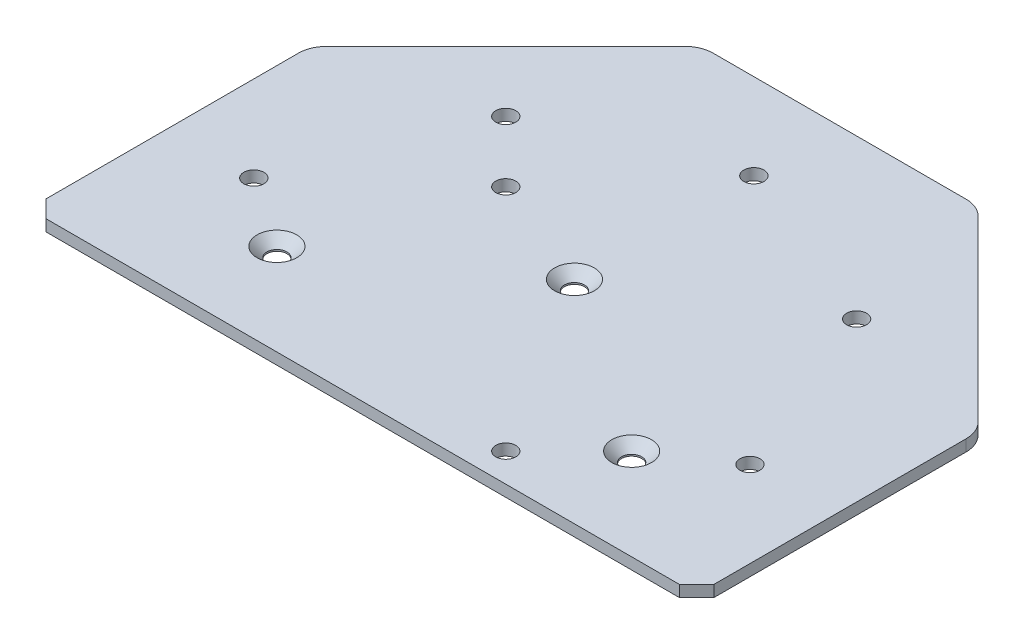
SolidWorks part; units mm, degrees
material "1060 Alloy"
ref_plane "Front Plane" through (0, 0, 0) normal (0, 0, 1) x (1, 0, 0)
ref_plane "Top Plane" through (0, 0, 0) normal (0, 1, 0) x (1, 0, 0)
ref_plane "Right Plane" through (0, 0, 0) normal (1, 0, 0) x (0, 0, -1)
sketch "Sketch2" plane through (0, 0, 0) normal (0, 1, 0) x (1, 0, 0)
  line L0 (-58.3553, 0) -> (58.3553, 0)
  line L1 (58.3553, 0) -> (58.3553, 49.1716)
  line L2 (58.3553, 49.1716) -> (24.1716, 83.3553)
  line L3 (24.1716, 83.3553) -> (-24.1716, 83.3553)
  line L4 (0, 83.3553) -> (0, 0) construction
  line L5 (-58.3553, 49.1716) -> (-24.1716, 83.3553)
  line L6 (-58.3553, 0) -> (-58.3553, 49.1716)
  line L7 (-57.9727, 49.5543) -> (-24.5543, 82.9727) construction
  line L8 (23.6304, 83.3553) -> (-23.6304, 83.3553) construction
extrude "Boss-Extrude1" add sketch "Sketch2" along normal blind 2
sketch "Sketch3" plane through (0, 0, 0) normal (0, -1, 0) x (1, 0, 0)
  circle A0 centre (-43.3553, -24.3152) radius 1.75
  circle A1 centre (-30.6569, -55.6569) radius 1.75
  circle A2 centre (0, -68.3553) radius 1.75
  circle A3 centre (30.6569, -55.6569) radius 1.75
  circle A4 centre (43.3553, -24.3152) radius 1.75
  dimension "D1" = 3.5
extrude "Cut-Extrude1" cut sketch "Sketch3" against normal up to next
chamfer "Chamfer1" distance 3 angle 45 2 edges at (58.3553, 1, 0) (-58.3553, 1, 0)
fillet "Fillet1" radius 5 4 edges at (58.3553, 1, -49.1716) (24.1716, 1, -83.3553) (-24.1716, 1, -83.3553) (-58.3553, 1, -49.1716)
sketch "Sketch4" plane through (0, 2, 0) normal (0, 1, 0) x (1, 0, 0)
  line L0 (0, 0) -> (0, 45) construction
  line L1 (0, 45) -> (-20, 45) construction
  line L2 (0, 5) -> (20, 5) construction
  line L4 (-55.3553, 0) -> (55.3553, 0) construction
  circle A0 centre (-20, 45) radius 1.75
  circle A1 centre (20, 5) radius 1.75
  dimension "D2" = 3.5
  dimension "D3" = 40
  dimension "D1" = 40
  dimension "D4" = 5
extrude "Cut-Extrude2" cut sketch "Sketch4" against normal up to next
sketch "Sketch5" plane through (0, 2, 0) normal (0, 1, 0) x (1, 0, 0)
  line L0 (0, 0) -> (0, 37) construction
  line L1 (-31, 16) -> (0, 16) construction
  line L2 (0, 16) -> (31, 16) construction
  circle A0 centre (0, 37) radius 1.75
  circle A1 centre (-31, 16) radius 1.75
  circle A2 centre (31, 16) radius 1.75
  dimension "D3" = 62
  dimension "D1" = 3.5
  dimension "D2" = 37
  dimension "D4" = 21
extrude "Cut-Extrude3" cut sketch "Sketch5" against normal up to next
hole_wizard "CSK for M3 Hex Socket Countersunk Head Screw1" positions "3DSketch1" profile "Sketch6" countersink size "M3" standard "DIN" end condition through all
sketch3d "3DSketch1"
  line L0 (0, 0, -37) -> (0, 2, -37) construction
  line L1 (-31, 0, -16) -> (-31, 2, -16) construction
  line L2 (31, 0, -16) -> (31, 2, -16) construction
  point P0 (0, 2, -37)
  point P4 (-31, 2, -16)
  point P8 (31, 2, -16)
sketch "Sketch6" plane through (0, 2, -37) normal (1, 0, 0) x (0, 0, 1)
  line L0 (0, 0) -> (0, 2)
  line L1 (0, 2) -> (1.7, 2)
  line L2 (1.7, 2) -> (1.7, 1.77)
  line L3 (1.7, 1.77) -> (3.47, 0)
  line L5 (3.47, 0) -> (0, 0)
  line L6 (-1.7, 1.77) -> (-3.47, 0) construction
  line L11 (0, -6.35) -> (0, 107.95) construction
  dimension "Thru Hole Dia." = 3.4
  dimension "Thru Hole Depth" = 2
  dimension "Near C'Sink Dia." = 6.94
  dimension "Near C'Sink Angle" = 90
